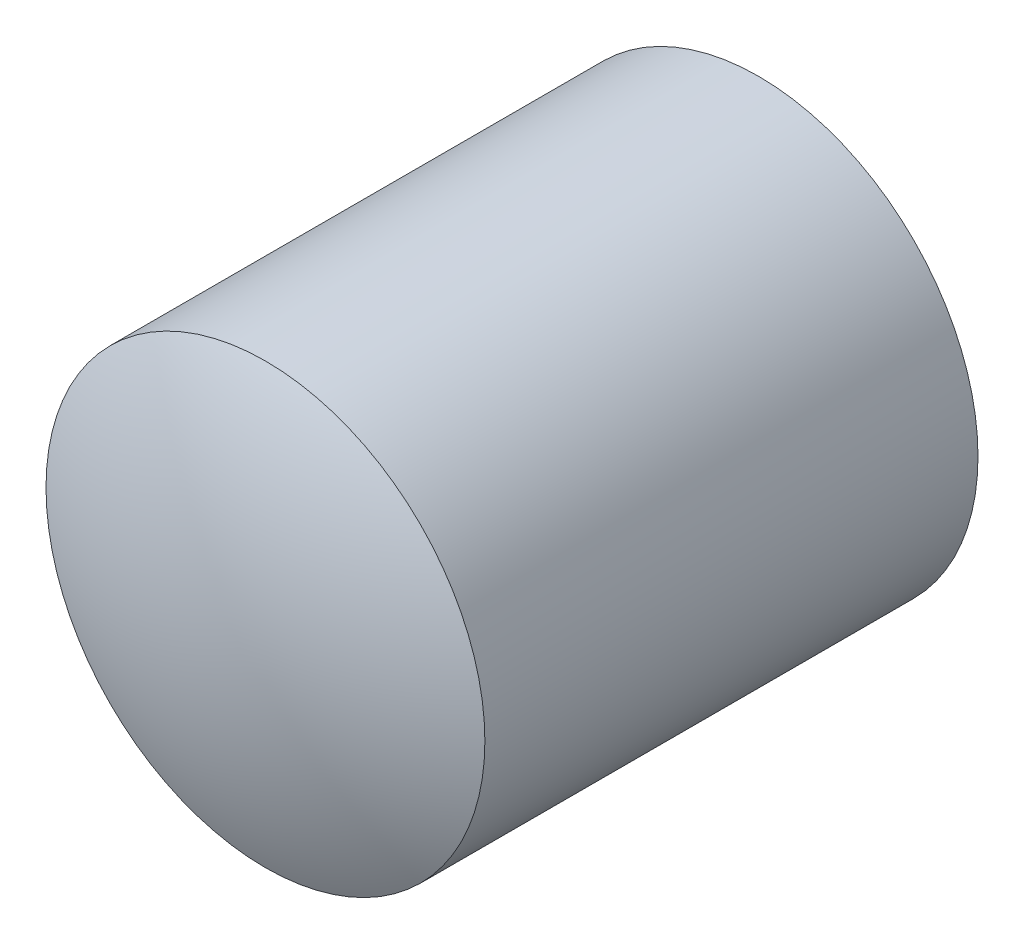
SolidWorks part; units mm, degrees
ref_plane "Front Plane" through (0, 0, 0) normal (0, 0, 1) x (1, 0, 0)
ref_plane "Top Plane" through (0, 0, 0) normal (0, 1, 0) x (1, 0, 0)
ref_plane "Right Plane" through (0, 0, 0) normal (1, 0, 0) x (0, 0, -1)
sketch "Sketch3" plane through (0, 0, 0) normal (1, 0, 0) x (0, 0, -1)
  line L0 (-3.6721, 0) -> (3.6721, 0)
  line L1 (0, 0) -> (0, 2.7175)
  line L2 (-3.0533, 2.7175) -> (3.0533, 2.7175)
  line L3 (0, 0) -> (-2.6039, 0)
  arc A0 (3.6721, 0) -> (3.0533, 2.7175) centre (-2.6039, 0) ccw
  arc A1 (-3.6721, 0) -> (-3.0533, 2.7175) centre (2.6039, 0) cw
  dimension "D1" = 3.6721
  dimension "D2" = 2.7175
  dimension "D3" = 3.0533
  dimension "D4" = 2.6039
revolve "Revolve1" add sketch "Sketch3" angle 360 about L3
equation "\"T_edge\" = \"R\" * 0.973"
equation "\"R\" = \"gloabl_scale\" * 6.276mm"
equation "\"dT_c\"= \"R\" * ( 1 - sqr ( 1 - \"h\" ^ 2 / \"R\" ^ 2 ) )"
equation "\"h\" = 0.433 * \"R\""
equation "\"gloabl_scale\"= 1"
equation "\"x_sphere_origin\"= \"R\" - \"dT_c\" - \"T_edge\" / 2"
equation "\"T_c\"= \"T_edge\" + 2 * \"dT_c\""
equation "\"D1@Sketch3\"=\"T_c\" / 2"
equation "\"D2@Sketch3\"=\"h\""
equation "\"D3@Sketch3\"=\"T_edge\" / 2"
equation "\"D4@Sketch3\"=\"x_sphere_origin\""
